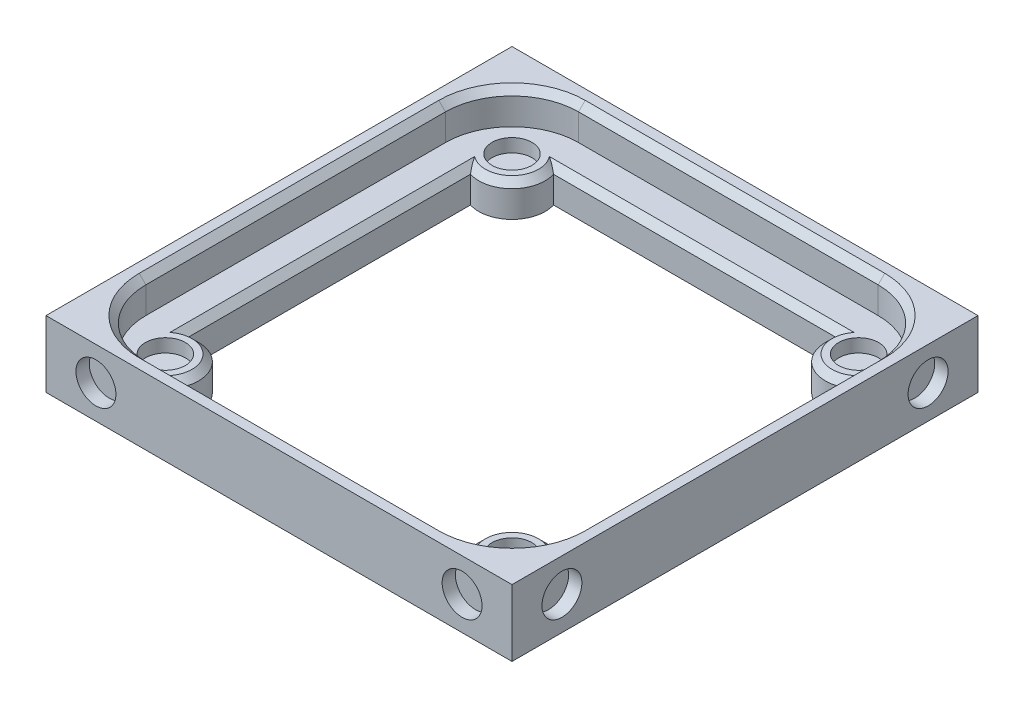
SolidWorks part; units mm, degrees
ref_plane "Front Plane" through (0, 0, 0) normal (0, 0, 1) x (1, 0, 0)
ref_plane "Top Plane" through (0, 0, 0) normal (0, 1, 0) x (1, 0, 0)
ref_plane "Right Plane" through (0, 0, 0) normal (1, 0, 0) x (0, 0, -1)
sketch "Sketch1" plane through (0, 0, 0) normal (0, 1, 0) x (1, 0, 0)
  line L1 (0, 0) -> (70, 0)
  line L2 (0, 0) -> (0, 70)
  line L3 (0, 70) -> (70, 70)
  line L4 (70, 0) -> (70, 70)
  dimension "D1" = 70
  dimension "D2" = 70
extrude "Boss-Extrude2" add sketch "Sketch1" along normal blind 7
sketch "Sketch3" plane through (0, 7, 0) normal (0, 1, 0) x (1, 0, 0)
  line L8 (2.5, 67.5) -> (2.5, 2.5)
  line L9 (2.5, 2.5) -> (67.5, 2.5)
  line L10 (67.5, 2.5) -> (67.5, 67.5)
  line L11 (67.5, 67.5) -> (2.5, 67.5)
  line L12 (2.5, 57.5) -> (2.5, 12.5)
  line L13 (12.5, 2.5) -> (57.5, 2.5)
  line L14 (67.5, 12.5) -> (67.5, 57.5)
  line L15 (57.5, 67.5) -> (12.5, 67.5)
  arc A0 (2.5, 12.5) -> (12.5, 2.5) centre (12.5, 12.5) ccw
  arc A1 (57.5, 2.5) -> (67.5, 12.5) centre (57.5, 12.5) ccw
  arc A2 (67.5, 57.5) -> (57.5, 67.5) centre (57.5, 57.5) ccw
  arc A3 (2.5, 57.5) -> (12.5, 67.5) centre (12.5, 57.5) cw
  dimension "D2" = 10
  dimension "D1" = 2.5
extrude "Cut-Extrude1" cut sketch "Sketch3" against normal blind 5
sketch "Sketch9" plane through (0, 0, 0) normal (0, -1, 0) x (1, 0, 0)
  line L1 (0, -70) -> (70, -70)
  line L2 (0, -70) -> (0, 0)
  line L3 (0, 0) -> (70, 0)
  line L4 (70, -70) -> (70, 0)
extrude "Boss-Extrude3" add sketch "Sketch9" along normal blind 5
sketch "Sketch20" plane through (0, 2, 0) normal (0, 1, 0) x (1, 0, 0)
  line L0 (35, 35) -> (8.9645, 61.0355) construction
  line L19 (12.5, 7.5) -> (57.5, 7.5)
  line L20 (62.5, 12.5) -> (62.5, 57.5)
  line L21 (57.5, 62.5) -> (12.5, 62.5)
  line L22 (7.5, 57.5) -> (7.5, 12.5)
  line L23 (13.7452, 7.5) -> (56.2548, 7.5)
  line L24 (62.5, 13.7452) -> (62.5, 56.2548)
  line L25 (56.2548, 62.5) -> (13.7452, 62.5)
  line L26 (7.5, 56.2548) -> (7.5, 13.7452)
  arc A0 (56.2548, 62.5) -> (62.5, 56.2548) centre (61.0355, 61.0355) ccw
  arc A1 (62.5, 13.7452) -> (56.2548, 7.5) centre (61.0355, 8.9645) ccw
  arc A2 (13.7452, 7.5) -> (7.5, 13.7452) centre (8.9645, 8.9645) ccw
  circle A4 centre (8.9645, 61.0355) radius 3
  circle A5 centre (8.9645, 8.9645) radius 3
  circle A6 centre (61.0355, 8.9645) radius 3
  circle A7 centre (61.0355, 61.0355) radius 3
  arc A21 (7.5, 56.2548) -> (13.7452, 62.5) centre (8.9645, 61.0355) ccw
  arc A24 (7.5, 12.5) -> (12.5, 7.5) centre (12.5, 12.5) ccw
  arc A25 (57.5, 7.5) -> (62.5, 12.5) centre (57.5, 12.5) ccw
  arc A26 (62.5, 57.5) -> (57.5, 62.5) centre (57.5, 57.5) ccw
  arc A27 (12.5, 62.5) -> (7.5, 57.5) centre (12.5, 57.5) ccw
  point P8 (35, 35)
  point P16 (0, 0)
  dimension "D2" = 6
  dimension "D3" = 4
  dimension "D4" = 36.8198
  dimension "D1" = 5
extrude "Cut-Extrude11" cut sketch "Sketch20" against normal through all contours L23 A1 L24 A0 L25 A21 L26 A2
sketch "Sketch21" plane through (0, 2, 0) normal (0, 1, 0) x (1, 0, 0)
  circle A0 centre (8.9645, 61.0355) radius 3
  circle A1 centre (61.0355, 61.0355) radius 3
  circle A2 centre (61.0355, 8.9645) radius 3
  circle A3 centre (8.9645, 8.9645) radius 3
extrude "Cut-Extrude12" cut sketch "Sketch21" against normal blind 2 contours A0 | A1 | A2 | A3
chamfer "Chamfer3" distance 1 angle 45 16 edges at (35, 7, -2.5) (64.5711, 7, -5.4289) (5.4289, 7, -5.4289) (67.5, 7, -35) (2.5, 7, -35) (64.5711, 7, -64.5711) (5.4289, 7, -64.5711) (35, 7, -67.5) (12.5, 2, -12.5) (35, 2, -7.5) (57.5, 2, -12.5) (62.5, 2, -35) (57.5, 2, -57.5) (7.5, 2, -35) (12.5, 2, -57.5) (35, 2, -62.5)
sketch "Sketch22" plane through (0, -5, 0) normal (0, -1, 0) x (1, 0, 0)
  line L0 (7.5, -13.7452) -> (7.5, -56.2548)
  line L1 (0, 0) -> (70, 0)
  line L2 (0, 0) -> (0, -70)
  line L3 (0, -70) -> (70, -70)
  line L4 (70, 0) -> (70, -70)
  line L6 (13.7452, -62.5) -> (56.2548, -62.5)
  line L8 (62.5, -56.2548) -> (62.5, -13.7452)
  line L10 (56.2548, -7.5) -> (13.7452, -7.5)
  arc A0 (7.5, -13.7452) -> (13.7452, -7.5) centre (8.9645, -8.9645) ccw
  arc A1 (56.2548, -7.5) -> (62.5, -13.7452) centre (61.0355, -8.9645) ccw
  arc A2 (62.5, -56.2548) -> (56.2548, -62.5) centre (61.0355, -61.0355) ccw
  arc A3 (13.7452, -62.5) -> (7.5, -56.2548) centre (8.9645, -61.0355) ccw
extrude "Cut-Extrude13" cut sketch "Sketch22" against normal blind 2
ref_plane "Plane2" through (0, 0, -35) normal (0, 0, 1) x (1, 0, 0)
ref_plane "Plane3" through (35, 0, 0) normal (-1, 0, 0) x (0, 0, 1)
sketch "Sketch27" plane through (0, 0, 0) normal (-1, 0, 0) x (0, 0, 1)
  line L0 (-70, -3) -> (-70, 7)
  line L1 (-70, 7) -> (-70, 2)
  line L2 (-70, 2) -> (-62.5, 2)
  line L3 (-35, -5.5) -> (-35, 5.5) construction
  circle A0 centre (-62.5, 2) radius 3
  circle A1 centre (-7.5, 2) radius 3
extrude "Cut-Extrude27" cut sketch "Sketch27" against normal blind 2
mirror "Mirror4" about plane through (35, 0, 0) normal (-1, 0, 0) of "Cut-Extrude27"
sketch "Sketch28" plane through (0, 0, 0) normal (0, 0, 1) x (1, 0, 0)
  line L0 (0, -3) -> (0, 7)
  line L1 (0, 7) -> (0, 2)
  line L2 (0, 2) -> (7.5, 2)
  line L3 (35, 5.5) -> (35, -5.5) construction
  circle A0 centre (7.5, 2) radius 3
  circle A1 centre (62.5, 2) radius 3
extrude "Cut-Extrude28" cut sketch "Sketch28" against normal blind 2
mirror "Mirror5" about plane through (0, 0, -35) normal (0, 0, 1) of "Cut-Extrude28"
